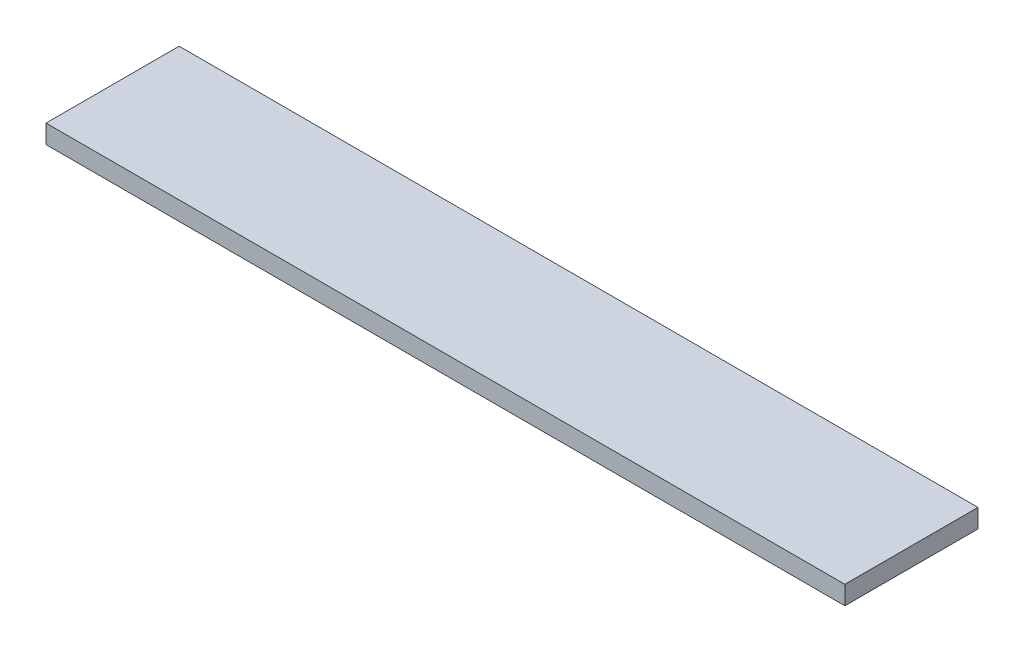
SolidWorks part; units mm, degrees
ref_plane "Front Plane" through (0, 0, 0) normal (0, 0, 1) x (1, 0, 0)
ref_plane "Top Plane" through (0, 0, 0) normal (0, 1, 0) x (1, 0, 0)
ref_plane "Right Plane" through (0, 0, 0) normal (1, 0, 0) x (0, 0, -1)
sketch "Sketch1" plane through (0, 0, 0) normal (0, 1, 0) x (1, 0, 0)
  line L1 (-15, -2.5) -> (15, -2.5)
  line L2 (-15, -2.5) -> (-15, 2.5)
  line L3 (-15, 2.5) -> (15, 2.5)
  line L4 (15, -2.5) -> (15, 2.5)
  line L5 (-15, -2.5) -> (15, 2.5) construction
  line L6 (-15, 2.5) -> (15, -2.5) construction
  point P0 (0, 0)
  dimension "D1" = 5
  dimension "D2" = 30
extrude "Boss-Extrude1" add sketch "Sketch1" along normal blind 0.7
